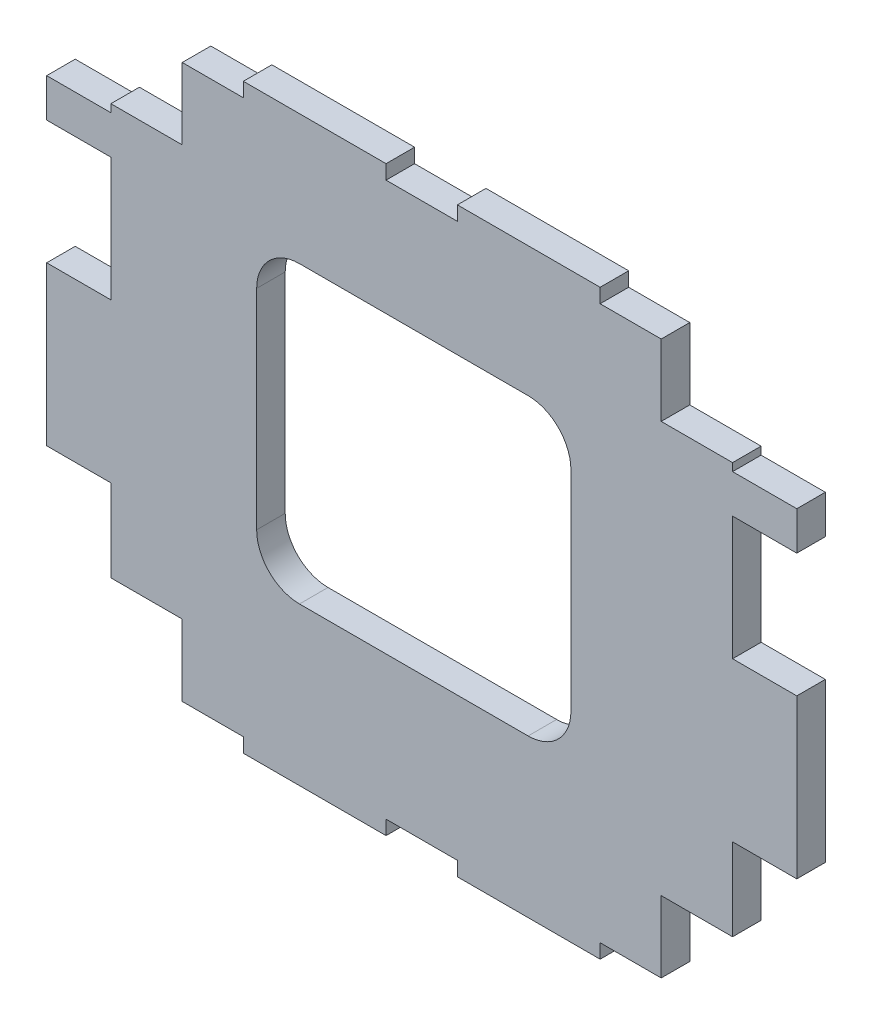
SolidWorks part; units mm, degrees
ref_plane "前视基准面" through (0, 0, 0) normal (0, 0, 1) x (1, 0, 0)
ref_plane "上视基准面" through (0, 0, 0) normal (0, 1, 0) x (1, 0, 0)
ref_plane "右视基准面" through (0, 0, 0) normal (1, 0, 0) x (0, 0, -1)
sketch "Model" plane through (0, 0, 0) normal (0, 0, 1) x (1, 0, 0)
  line L0 (57.8081, 35.905) -> (41.7881, 35.905)
  line L1 (41.7881, 15.255) -> (57.8081, 15.255)
  line L2 (60.8081, 32.905) -> (60.8081, 18.255)
  line L3 (38.7881, 32.905) -> (38.7881, 18.255)
  line L4 (33.5739, 44.005) -> (37.8539, 44.005)
  line L5 (37.8539, 44.005) -> (37.8539, 45.0054)
  line L6 (37.8539, 45.0054) -> (47.8539, 45.0054)
  line L7 (47.8539, 45.0054) -> (47.8539, 44.005)
  line L8 (47.8539, 44.005) -> (52.8539, 44.005)
  line L9 (52.8539, 44.005) -> (52.8539, 45.0054)
  line L10 (52.8539, 45.0054) -> (62.8539, 45.0054)
  line L11 (62.8539, 45.0054) -> (62.8539, 44.005)
  line L12 (62.8539, 44.005) -> (67.1339, 44.005)
  line L13 (33.5739, 5.2303) -> (37.8539, 5.2303)
  line L14 (37.8539, 5.2303) -> (37.8539, 4.2299)
  line L15 (37.8539, 4.2299) -> (47.8539, 4.2299)
  line L16 (47.8539, 4.2299) -> (47.8539, 5.2303)
  line L17 (47.8539, 5.2303) -> (52.8539, 5.2303)
  line L18 (52.8539, 5.2303) -> (52.8539, 4.2299)
  line L19 (52.8539, 4.2299) -> (62.8539, 4.2299)
  line L20 (62.8539, 4.2299) -> (62.8539, 5.2303)
  line L21 (62.8539, 5.2303) -> (67.1339, 5.2303)
  line L22 (24.0739, 35.7595) -> (24.0739, 38.4571)
  line L23 (24.0739, 15.994) -> (24.0739, 27.1011)
  line L24 (28.5739, 10.2303) -> (33.5739, 10.2303)
  line L25 (28.5739, 10.2303) -> (28.5739, 15.994)
  line L27 (28.5739, 27.1011) -> (28.5739, 35.7595)
  line L28 (28.5739, 35.7595) -> (24.0739, 35.7595)
  line L29 (24.0739, 38.4571) -> (28.5739, 38.4571)
  line L31 (24.0739, 15.994) -> (28.5739, 15.994)
  line L32 (24.0739, 27.1011) -> (28.5739, 27.1011)
  line L33 (33.5739, 10.2303) -> (33.5739, 5.2303)
  line L34 (33.5739, 44.005) -> (33.5739, 39.005)
  line L35 (33.5739, 39.005) -> (28.5739, 39.005)
  line L36 (28.5739, 39.005) -> (28.5739, 38.4571)
  line L38 (76.6339, 35.7595) -> (76.6339, 38.4571)
  line L39 (76.6339, 15.994) -> (76.6339, 27.1011)
  line L40 (72.1339, 10.2303) -> (67.1339, 10.2303)
  line L41 (72.1339, 10.2303) -> (72.1339, 15.994)
  line L43 (72.1339, 27.1011) -> (72.1339, 35.7595)
  line L44 (72.1339, 35.7595) -> (76.6339, 35.7595)
  line L45 (76.6339, 38.4571) -> (72.1339, 38.4571)
  line L47 (76.6339, 15.994) -> (72.1339, 15.994)
  line L48 (76.6339, 27.1011) -> (72.1339, 27.1011)
  line L49 (67.1339, 10.2303) -> (67.1339, 5.2303)
  line L50 (67.1339, 44.005) -> (67.1339, 39.005)
  line L51 (67.1339, 39.005) -> (72.1339, 39.005)
  line L52 (72.1339, 39.005) -> (72.1339, 38.4571)
  arc A0 (41.7881, 35.905) -> (38.7881, 32.905) centre (41.7881, 32.905) ccw
  arc A1 (57.8081, 15.255) -> (60.8081, 18.255) centre (57.8081, 18.255) ccw
  arc A2 (60.8081, 32.905) -> (57.8081, 35.905) centre (57.8081, 32.905) ccw
  arc A3 (38.7881, 18.255) -> (41.7881, 15.255) centre (41.7881, 18.255) ccw
extrude "凸台-拉伸1" add sketch "Model" along normal blind 2
